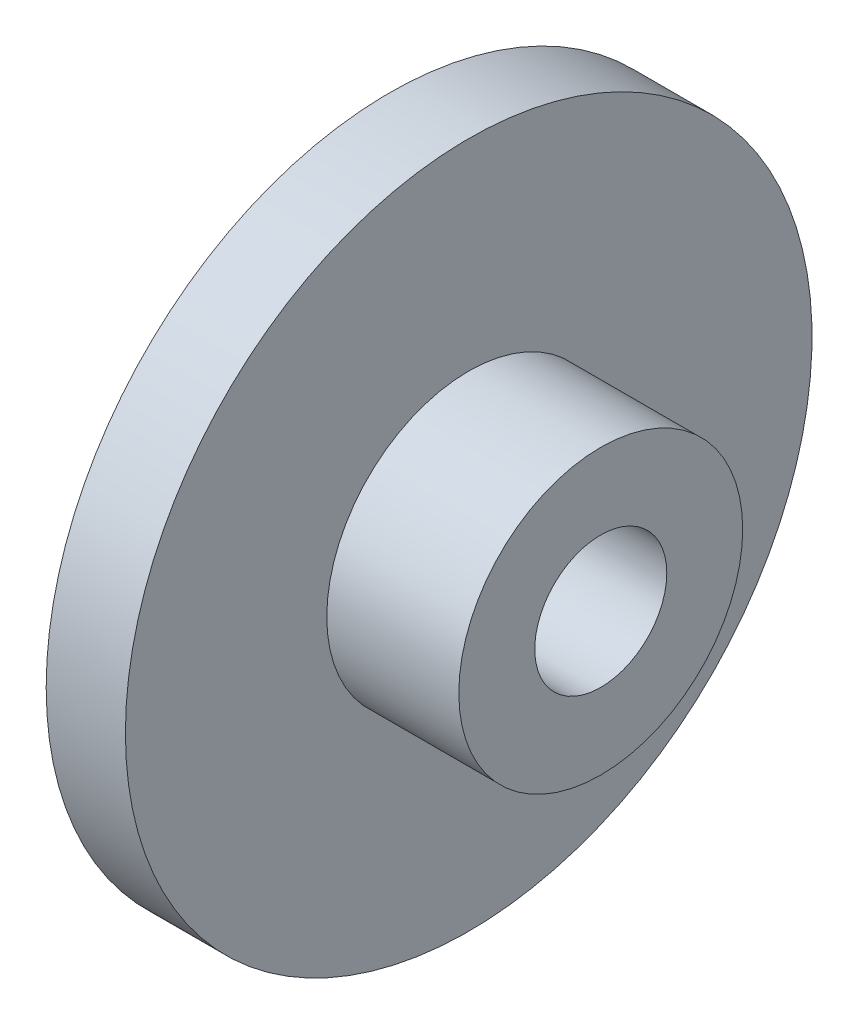
SolidWorks part; units mm, degrees
material "POM Acetal Copolymer"
ref_plane "Front Plane" through (0, 0, 0) normal (0, 0, 1) x (1, 0, 0)
ref_plane "Top Plane" through (0, 0, 0) normal (0, 1, 0) x (1, 0, 0)
ref_plane "Right Plane" through (0, 0, 0) normal (1, 0, 0) x (0, 0, -1)
sketch "Sketch1" plane through (0, 0, 0) normal (1, 0, 0) x (0, 0, -1)
  circle A0 centre (0, 0) radius 20.6375
  dimension "D1" = 41.275
extrude "Boss-Extrude1" add sketch "Sketch1" along normal blind 4.7625
sketch "Sketch2" plane through (4.7625, 0, 0) normal (1, 0, 0) x (0, 0, -1)
  circle A0 centre (0, 0) radius 8.5328
  dimension "D1" = 17.0656
extrude "Boss-Extrude2" add sketch "Sketch2" along normal blind 7.9375
hole_wizard "5/16 (0.3125) Diameter Hole1" positions "Sketch4" profile "Sketch3" hole size "5/16" standard "ANSI Inch"
sketch "Sketch4" plane through (12.7, 0, 0) normal (1, 0, 0) x (0, 0, -1)
  point P0 (0, 0)
sketch "Sketch3" plane through (12.7, 0, 0) normal (0, 1, 0) x (0, 0, -1)
  line L0 (0, 0) -> (0, 72.4887)
  line L1 (0, 72.4887) -> (3.9687, 70.104)
  line L2 (3.9687, 70.104) -> (3.9687, 0)
  line L5 (3.9687, 0) -> (0, 0)
  line L10 (0, 72.4887) -> (-3.9688, 70.104) construction
  line L11 (0, -6.35) -> (0, 107.95) construction
  dimension "Hole Dia." = 7.9375
  dimension "Hole Depth" = 70.104
  dimension "Drill Angle" = 118
